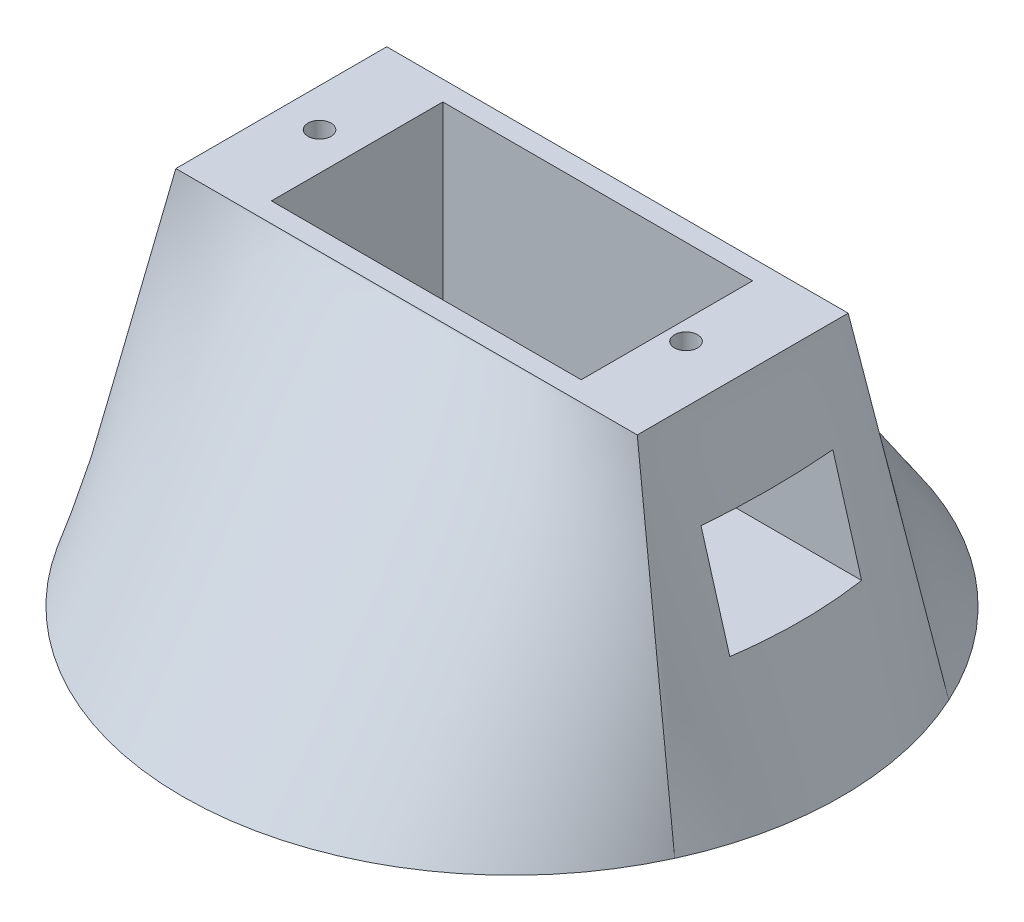
SolidWorks part; units mm, degrees
ref_plane "Front" through (0, 0, 0) normal (0, 0, 1) x (1, 0, 0)
ref_plane "Top" through (0, 0, 0) normal (0, 1, 0) x (1, 0, 0)
ref_plane "Right" through (0, 0, 0) normal (1, 0, 0) x (0, 0, -1)
sketch "Sketch1" plane through (0, 0, 0) normal (0, 1, 0) x (1, 0, 0)
  line L1 (-17.5, -8) -> (17.5, -8)
  line L2 (-17.5, -8) -> (-17.5, 8)
  line L3 (-17.5, 8) -> (17.5, 8)
  line L4 (17.5, -8) -> (17.5, 8)
  line L5 (-17.5, -8) -> (17.5, 8) construction
  line L6 (-17.5, 8) -> (17.5, -8) construction
  point P0 (0, 0)
  dimension "D1" = 35
  dimension "D2" = 16
extrude "Boss-Extrude1" add sketch "Sketch1" along normal blind 24
sketch "Sketch7" plane through (0, 0, 0) normal (0, -1, 0) x (1, 0, 0)
  circle A0 centre (0, 0) radius 25
  point P0 (0, 0)
  dimension "D1" = 50
sketch "Sketch8" plane through (0, 24, 0) normal (0, 1, 0) x (1, 0, 0)
  line L1 (17.5, -8) -> (-17.5, -8)
  line L2 (17.5, -8) -> (17.5, 8)
  line L3 (17.5, 8) -> (-17.5, 8)
  line L4 (-17.5, -8) -> (-17.5, 8)
  line L5 (17.5, -8) -> (-17.5, 8) construction
  line L6 (17.5, 8) -> (-17.5, -8) construction
  point P0 (0, 0)
loft "Loft1" add profiles "Sketch8", "Sketch7"
sketch "Sketch3" plane through (0, 24, 0) normal (0, -1, 0) x (1, 0, 0)
  line L1 (-11.75, -6.5) -> (11.75, -6.5)
  line L2 (-11.75, -6.5) -> (-11.75, 6.5)
  line L3 (-11.75, 6.5) -> (11.75, 6.5)
  line L4 (11.75, -6.5) -> (11.75, 6.5)
  line L5 (-11.75, -6.5) -> (11.75, 6.5) construction
  line L6 (-11.75, 6.5) -> (11.75, -6.5) construction
  point P0 (0, 0)
  dimension "D1" = 23.5
  dimension "D2" = 13
extrude "Cut-Extrude1" cut sketch "Sketch3" along normal blind 15.7
sketch "Sketch5" plane through (0, 24, 0) normal (0, 1, 0) x (1, 0, 0)
  line L0 (11.75, 0) -> (13.2, 0) construction
  line L1 (11.75, 6.5) -> (11.75, -6.5) construction
  line L3 (-11.75, -6.5) -> (-11.75, 6.5) construction
  circle A0 centre (13.2, 0) radius 0.875
  circle A1 centre (-14.6, 0) radius 0.875
  dimension "D2" = 1.75
  dimension "D1" = 2.85
  dimension "D3" = 1.75
  dimension "D4" = 27.8
extrude "Cut-Extrude2" cut sketch "Sketch5" against normal blind 8 contours A0 | A1
sketch "Sketch9" plane through (11.75, 0, 0) normal (-1, 0, 0) x (0, 0, 1)
  line L0 (0, 24) -> (0, 13.7) construction
  line L1 (-6.5, 24) -> (6.5, 24) construction
  line L3 (-5, 9.95) -> (5, 9.95)
  line L4 (-5, 9.95) -> (-5, 17.45)
  line L5 (-5, 17.45) -> (5, 17.45)
  line L6 (5, 9.95) -> (5, 17.45)
  line L7 (-5, 9.95) -> (5, 17.45) construction
  line L8 (-5, 17.45) -> (5, 9.95) construction
  dimension "D1" = 10.3
  dimension "D2" = 10
  dimension "D3" = 7.5
extrude "Cut-Extrude3" cut sketch "Sketch9" against normal up to surface (9.7697 mm away)
fillet "Fillet1" [suppressed] radius 1.5
